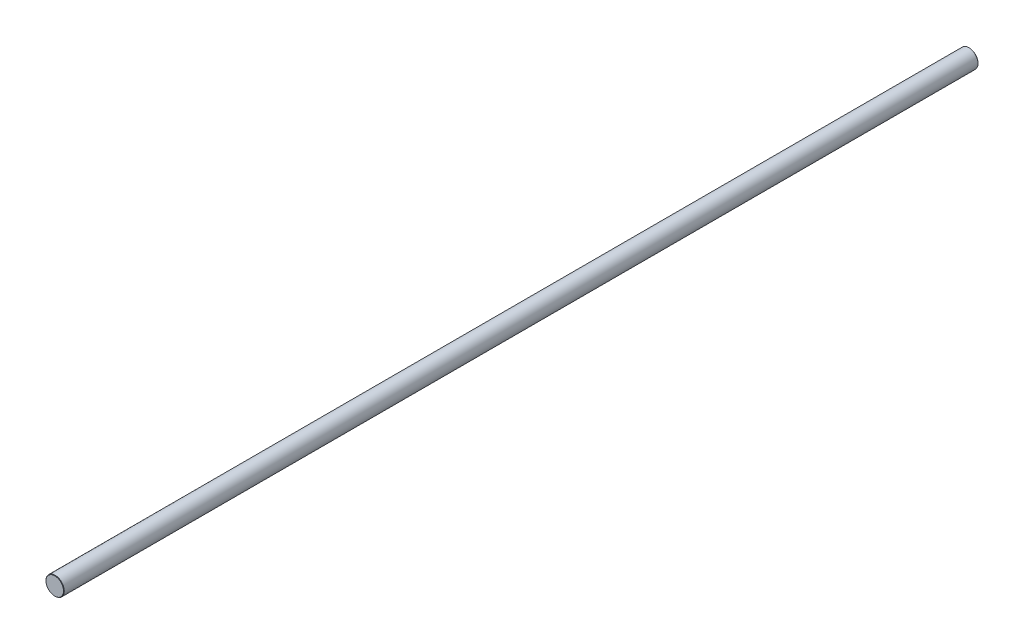
SolidWorks part; units mm, degrees
ref_plane "Front Plane" through (0, 0, 0) normal (0, 0, 1) x (1, 0, 0)
ref_plane "Top Plane" through (0, 0, 0) normal (0, 1, 0) x (1, 0, 0)
ref_plane "Right Plane" through (0, 0, 0) normal (1, 0, 0) x (0, 0, -1)
sketch "Sketch1" plane through (0, 0, 0) normal (1, 0, 0) x (0, 0, -1)
  line L0 (-200, 0) -> (200, 0) construction
  line L1 (0, -4) -> (0, 4) construction
  point P4 (0, 0)
  point P8 (0, 0)
sketch "Sketch2" plane through (0, 0, 0) normal (0, 0, 1) x (1, 0, 0)
  circle A0 centre (0, 0) radius 4
extrude "Boss-Extrude1" add sketch "Sketch2" along normal up to vertex (200 mm away) and the other way up to vertex (200 mm away) up to point (0, 0, 200) other way up to point (0, 0, -200)
chamfer "Chamfer1" distance 0.16 angle 45 2 edges at (4, 0, -200) (4, 0, 200)
equation "\"D1@Chamfer1\"=\"Diameter@Sketch1\"*.02"
